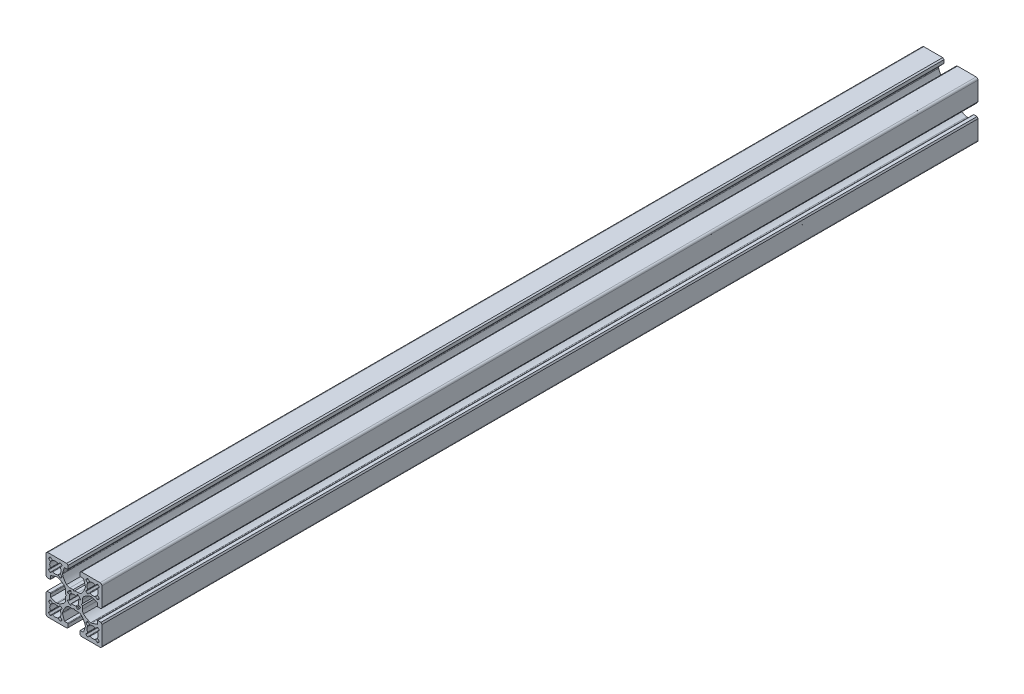
SolidWorks part; units mm, degrees
ref_plane "정면" through (0, 0, 0) normal (0, 0, 1) x (1, 0, 0)
ref_plane "윗면" through (0, 0, 0) normal (0, 1, 0) x (1, 0, 0)
ref_plane "우측면" through (0, 0, 0) normal (1, 0, 0) x (0, 0, -1)
sketch "Model" plane through (0, 0, 0) normal (0, 0, 1) x (1, 0, 0)
  line L0 (465.6218, 205.5838) -> (465.6218, 209.9838) construction
  line L1 (463.4218, 207.7838) -> (467.8218, 207.7838) construction
  line L2 (462.8793, 206.102) -> (462.1388, 205.3614)
  line L3 (463.1994, 204.3007) -> (463.94, 205.0413)
  line L4 (467.3037, 205.0413) -> (468.0443, 204.3007)
  line L5 (469.1049, 205.3614) -> (468.3643, 206.102)
  line L6 (468.3643, 209.4657) -> (469.1049, 210.2063)
  line L7 (468.0443, 211.2669) -> (467.3037, 210.5263)
  line L8 (463.94, 210.5263) -> (463.1994, 211.2669)
  line L9 (462.1388, 210.2063) -> (462.8793, 209.4657)
  line L10 (463.4211, 187.7832) -> (467.8211, 187.7829) construction
  line L11 (465.6212, 189.9831) -> (465.6209, 185.5831) construction
  line L12 (462.8787, 189.4651) -> (462.1382, 190.2057)
  line L13 (463.1989, 191.2663) -> (463.9394, 190.5257)
  line L14 (467.3031, 190.5254) -> (468.0438, 191.2659)
  line L15 (469.1043, 190.2052) -> (468.3637, 189.4647)
  line L16 (468.3634, 186.101) -> (469.1039, 185.3604)
  line L17 (468.0432, 184.2998) -> (467.3027, 185.0404)
  line L18 (463.939, 185.0407) -> (463.1984, 184.3002)
  line L19 (462.1378, 185.3609) -> (462.8784, 186.1014)
  line L20 (448.3673, 189.4651) -> (449.1078, 190.2057)
  line L21 (448.0471, 191.2663) -> (447.3066, 190.5257)
  line L22 (443.9429, 190.5254) -> (443.2023, 191.2659)
  line L23 (442.1417, 190.2052) -> (442.8823, 189.4647)
  line L24 (442.8826, 186.101) -> (442.1421, 185.3604)
  line L25 (443.2028, 184.2998) -> (443.9433, 185.0404)
  line L26 (447.307, 185.0407) -> (448.0476, 184.3002)
  line L27 (449.1082, 185.3609) -> (448.3676, 186.1014)
  line L28 (445.6248, 189.9831) -> (445.6251, 185.5831) construction
  line L29 (447.825, 187.7832) -> (443.425, 187.7829) construction
  line L30 (447.8242, 207.7838) -> (443.4242, 207.7838) construction
  line L31 (445.6242, 205.5838) -> (445.6242, 209.9838) construction
  line L32 (471.0819, 197.7838) -> (439.4, 197.7838) construction
  line L33 (455.6242, 181.8427) -> (455.6242, 213.7801) construction
  line L34 (457.2103, 201.0212) -> (457.0767, 200.2802)
  line L35 (454.1716, 200.2802) -> (454.0381, 201.0212)
  line L36 (452.3868, 199.37) -> (453.1278, 199.2364)
  line L37 (453.1278, 196.3313) -> (452.3868, 196.1977)
  line L38 (454.0381, 194.5465) -> (454.1716, 195.2874)
  line L39 (457.0767, 195.2874) -> (457.2103, 194.5465)
  line L40 (458.8615, 196.1977) -> (458.1206, 196.3313)
  line L41 (458.1206, 199.2364) -> (458.8615, 199.37)
  line L42 (448.3667, 206.102) -> (449.1073, 205.3614)
  line L43 (448.0466, 204.3007) -> (447.306, 205.0413)
  line L44 (443.9423, 205.0413) -> (443.2018, 204.3007)
  line L45 (442.1411, 205.3614) -> (442.8817, 206.102)
  line L46 (442.8817, 209.4657) -> (442.1411, 210.2063)
  line L47 (443.2018, 211.2669) -> (443.9423, 210.5263)
  line L48 (447.306, 210.5263) -> (448.0466, 211.2669)
  line L49 (449.1073, 210.2063) -> (448.3667, 209.4657)
  line L50 (459.5742, 182.7838) -> (458.7742, 183.2838)
  line L51 (458.7742, 183.2838) -> (458.7742, 184.9838)
  line L52 (459.0742, 185.2838) -> (460.7242, 185.2838)
  line L53 (460.7242, 185.2838) -> (461.7118, 188.3356)
  line L54 (457.842, 193.2838) -> (456.1242, 193.2838)
  line L55 (456.1242, 193.2838) -> (455.6242, 193.7838)
  line L56 (455.6242, 193.7838) -> (455.1242, 193.2838)
  line L57 (455.1242, 193.2838) -> (453.4063, 193.2838)
  line L58 (449.5366, 188.3356) -> (450.5242, 185.2838)
  line L59 (450.5242, 185.2838) -> (452.1742, 185.2838)
  line L60 (452.4742, 184.9838) -> (452.4742, 183.2838)
  line L61 (452.4742, 183.2838) -> (451.6742, 182.7838)
  line L62 (451.6742, 182.7838) -> (441.6242, 182.7838)
  line L63 (440.6242, 183.7838) -> (440.6242, 193.8338)
  line L64 (440.6242, 193.8338) -> (441.1242, 194.6338)
  line L65 (441.1242, 194.6338) -> (442.8242, 194.6338)
  line L66 (443.1242, 194.3338) -> (443.1242, 192.6838)
  line L67 (443.1242, 192.6838) -> (446.1759, 191.6962)
  line L68 (451.1242, 195.566) -> (451.1242, 197.2838)
  line L69 (451.1242, 197.2838) -> (451.6242, 197.7838)
  line L70 (451.6242, 197.7838) -> (451.1242, 198.2838)
  line L71 (451.1242, 198.2838) -> (451.1242, 200.0017)
  line L72 (446.1759, 203.8714) -> (443.1242, 202.8838)
  line L73 (443.1242, 202.8838) -> (443.1242, 201.2338)
  line L74 (442.8242, 200.9338) -> (441.1242, 200.9338)
  line L75 (441.1242, 200.9338) -> (440.6242, 201.7338)
  line L76 (440.6242, 201.7338) -> (440.6242, 211.7838)
  line L77 (441.6242, 212.7838) -> (451.6742, 212.7838)
  line L78 (451.6742, 212.7838) -> (452.4742, 212.2838)
  line L79 (452.4742, 212.2838) -> (452.4742, 210.5838)
  line L80 (452.1742, 210.2838) -> (450.5242, 210.2838)
  line L81 (450.5242, 210.2838) -> (449.5366, 207.2321)
  line L82 (453.4063, 202.2838) -> (455.1242, 202.2838)
  line L83 (455.1242, 202.2838) -> (455.6242, 201.7838)
  line L84 (455.6242, 201.7838) -> (456.1242, 202.2838)
  line L85 (456.1242, 202.2838) -> (457.842, 202.2838)
  line L86 (461.7118, 207.2321) -> (460.7242, 210.2838)
  line L87 (460.7242, 210.2838) -> (459.0742, 210.2838)
  line L88 (458.7742, 210.5838) -> (458.7742, 212.2838)
  line L89 (458.7742, 212.2838) -> (459.5742, 212.7838)
  line L90 (459.5742, 212.7838) -> (469.6242, 212.7838)
  line L91 (470.6242, 211.7838) -> (470.6242, 201.7338)
  line L92 (470.6242, 201.7338) -> (470.1242, 200.9338)
  line L93 (470.1242, 200.9338) -> (468.4242, 200.9338)
  line L94 (468.1242, 201.2338) -> (468.1242, 202.8838)
  line L95 (468.1242, 202.8838) -> (465.0724, 203.8714)
  line L96 (460.1242, 200.0017) -> (460.1242, 198.2838)
  line L97 (460.1242, 198.2838) -> (459.6242, 197.7838)
  line L98 (459.6242, 197.7838) -> (460.1242, 197.2838)
  line L99 (460.1242, 197.2838) -> (460.1242, 195.566)
  line L100 (465.0724, 191.6962) -> (468.1242, 192.6838)
  line L101 (468.1242, 192.6838) -> (468.1242, 194.3338)
  line L102 (468.4242, 194.6338) -> (470.1242, 194.6338)
  line L103 (470.1242, 194.6338) -> (470.6242, 193.8338)
  line L104 (470.6242, 193.8338) -> (470.6242, 183.7838)
  line L105 (469.6242, 182.7838) -> (459.5742, 182.7838)
  arc A0 (462.8793, 206.102) -> (462.9358, 206.4477) centre (462.6672, 206.3141) ccw
  arc A1 (462.1388, 205.3614) -> (462.1172, 204.9611) centre (462.3509, 205.1493) ccw
  arc A2 (462.1172, 204.9611) -> (462.7991, 204.2792) centre (465.6218, 207.7838) ccw
  arc A3 (462.7991, 204.2792) -> (463.1994, 204.3007) centre (462.9873, 204.5129) ccw
  arc A4 (464.2857, 205.0978) -> (463.94, 205.0413) centre (464.1521, 204.8292) ccw
  arc A5 (464.2857, 205.0978) -> (466.9579, 205.0978) centre (465.6218, 207.7838) ccw
  arc A6 (467.3037, 205.0413) -> (466.9579, 205.0978) centre (467.0916, 204.8292) ccw
  arc A7 (468.0443, 204.3007) -> (468.4446, 204.2792) centre (468.2564, 204.5129) ccw
  arc A8 (468.4446, 204.2792) -> (469.1264, 204.9611) centre (465.6218, 207.7838) ccw
  arc A9 (469.1264, 204.9611) -> (469.1049, 205.3614) centre (468.8928, 205.1493) ccw
  arc A10 (468.3079, 206.4477) -> (468.3643, 206.102) centre (468.5765, 206.3141) ccw
  arc A11 (468.3079, 206.4477) -> (468.3079, 209.1199) centre (465.6218, 207.7838) ccw
  arc A12 (468.3643, 209.4657) -> (468.3079, 209.1199) centre (468.5765, 209.2536) ccw
  arc A13 (469.1049, 210.2063) -> (469.1264, 210.6066) centre (468.8928, 210.4184) ccw
  arc A14 (469.1264, 210.6066) -> (468.4446, 211.2884) centre (465.6218, 207.7838) ccw
  arc A15 (468.4446, 211.2884) -> (468.0443, 211.2669) centre (468.2564, 211.0548) ccw
  arc A16 (466.9579, 210.4699) -> (467.3037, 210.5263) centre (467.0916, 210.7385) ccw
  arc A17 (466.9579, 210.4699) -> (464.2857, 210.4699) centre (465.6218, 207.7838) ccw
  arc A18 (463.94, 210.5263) -> (464.2857, 210.4699) centre (464.1521, 210.7385) ccw
  arc A19 (463.1994, 211.2669) -> (462.7991, 211.2884) centre (462.9873, 211.0548) ccw
  arc A20 (462.7991, 211.2884) -> (462.1172, 210.6066) centre (465.6218, 207.7838) ccw
  arc A21 (462.1172, 210.6066) -> (462.1388, 210.2063) centre (462.3509, 210.4184) ccw
  arc A22 (462.9358, 209.1199) -> (462.8793, 209.4657) centre (462.6672, 209.2536) ccw
  arc A23 (462.9358, 209.1199) -> (462.9358, 206.4477) centre (465.6218, 207.7838) ccw
  arc A24 (462.9351, 189.1194) -> (462.8787, 189.4651) centre (462.6665, 189.253) ccw
  arc A25 (462.1167, 190.6061) -> (462.1382, 190.2057) centre (462.3503, 190.4179) ccw
  arc A26 (462.7986, 191.2879) -> (462.1167, 190.6061) centre (465.6211, 187.7831) ccw
  arc A27 (463.1989, 191.2663) -> (462.7986, 191.2879) centre (462.9868, 191.0542) ccw
  arc A28 (463.9394, 190.5257) -> (464.2852, 190.4692) centre (464.1516, 190.7378) ccw
  arc A29 (466.9574, 190.469) -> (464.2852, 190.4692) centre (465.6211, 187.7831) ccw
  arc A30 (466.9574, 190.469) -> (467.3031, 190.5254) centre (467.091, 190.7376) ccw
  arc A31 (468.4441, 191.2874) -> (468.0438, 191.2659) centre (468.2559, 191.0538) ccw
  arc A32 (469.1259, 190.6055) -> (468.4441, 191.2874) centre (465.6211, 187.7831) ccw
  arc A33 (469.1043, 190.2052) -> (469.1259, 190.6055) centre (468.8922, 190.4174) ccw
  arc A34 (468.3637, 189.4647) -> (468.3072, 189.119) centre (468.5758, 189.2525) ccw
  arc A35 (468.307, 186.4467) -> (468.3072, 189.119) centre (465.6211, 187.7831) ccw
  arc A36 (468.307, 186.4467) -> (468.3634, 186.101) centre (468.5756, 186.3131) ccw
  arc A37 (469.1254, 184.96) -> (469.1039, 185.3604) centre (468.8918, 185.1482) ccw
  arc A38 (468.4435, 184.2782) -> (469.1254, 184.96) centre (465.6211, 187.7831) ccw
  arc A39 (468.0432, 184.2998) -> (468.4435, 184.2782) centre (468.2554, 184.5119) ccw
  arc A40 (467.3027, 185.0404) -> (466.957, 185.0969) centre (467.0905, 184.8283) ccw
  arc A41 (464.2847, 185.0971) -> (466.957, 185.0969) centre (465.6211, 187.7831) ccw
  arc A42 (464.2847, 185.0971) -> (463.939, 185.0407) centre (464.1511, 184.8285) ccw
  arc A43 (462.798, 184.2787) -> (463.1984, 184.3002) centre (462.9862, 184.5123) ccw
  arc A44 (462.1162, 184.9606) -> (462.798, 184.2787) centre (465.6211, 187.7831) ccw
  arc A45 (462.1378, 185.3609) -> (462.1162, 184.9606) centre (462.3499, 185.1488) ccw
  arc A46 (462.8784, 186.1014) -> (462.9349, 186.4472) centre (462.6663, 186.3136) ccw
  arc A47 (462.9351, 189.1194) -> (462.9349, 186.4472) centre (465.6211, 187.7831) ccw
  arc A48 (448.3673, 189.4651) -> (448.3109, 189.1194) centre (448.5795, 189.253) ccw
  arc A49 (449.1078, 190.2057) -> (449.1293, 190.6061) centre (448.8957, 190.4179) ccw
  arc A50 (449.1293, 190.6061) -> (448.4474, 191.2879) centre (445.625, 187.7831) ccw
  arc A51 (448.4474, 191.2879) -> (448.0471, 191.2663) centre (448.2593, 191.0542) ccw
  arc A52 (446.9609, 190.4692) -> (447.3066, 190.5257) centre (447.0944, 190.7378) ccw
  arc A53 (446.9609, 190.4692) -> (444.2886, 190.469) centre (445.625, 187.7831) ccw
  arc A54 (443.9429, 190.5254) -> (444.2886, 190.469) centre (444.155, 190.7376) ccw
  arc A55 (443.2023, 191.2659) -> (442.8019, 191.2874) centre (442.9901, 191.0538) ccw
  arc A56 (442.8019, 191.2874) -> (442.1201, 190.6055) centre (445.625, 187.7831) ccw
  arc A57 (442.1201, 190.6055) -> (442.1417, 190.2052) centre (442.3538, 190.4174) ccw
  arc A58 (442.9388, 189.119) -> (442.8823, 189.4647) centre (442.6702, 189.2525) ccw
  arc A59 (442.9388, 189.119) -> (442.939, 186.4467) centre (445.625, 187.7831) ccw
  arc A60 (442.8826, 186.101) -> (442.939, 186.4467) centre (442.6704, 186.3131) ccw
  arc A61 (442.1421, 185.3604) -> (442.1206, 184.96) centre (442.3542, 185.1482) ccw
  arc A62 (442.1206, 184.96) -> (442.8025, 184.2782) centre (445.625, 187.7831) ccw
  arc A63 (442.8025, 184.2782) -> (443.2028, 184.2998) centre (442.9907, 184.5119) ccw
  arc A64 (444.2891, 185.0969) -> (443.9433, 185.0404) centre (444.1555, 184.8283) ccw
  arc A65 (444.2891, 185.0969) -> (446.9613, 185.0971) centre (445.625, 187.7831) ccw
  arc A66 (447.307, 185.0407) -> (446.9613, 185.0971) centre (447.0949, 184.8285) ccw
  arc A67 (448.0476, 184.3002) -> (448.448, 184.2787) centre (448.2598, 184.5123) ccw
  arc A68 (448.448, 184.2787) -> (449.1298, 184.9606) centre (445.625, 187.7831) ccw
  arc A69 (449.1298, 184.9606) -> (449.1082, 185.3609) centre (448.8961, 185.1488) ccw
  arc A70 (448.3111, 186.4472) -> (448.3676, 186.1014) centre (448.5797, 186.3136) ccw
  arc A71 (448.3111, 186.4472) -> (448.3109, 189.1194) centre (445.625, 187.7831) ccw
  arc A72 (458.8615, 199.37) -> (459.0666, 199.8178) centre (458.8083, 199.6652) ccw
  arc A73 (459.0666, 199.8178) -> (457.6582, 201.2262) centre (455.623, 197.7827) ccw
  arc A74 (457.6582, 201.2262) -> (457.2103, 201.0212) centre (457.5055, 200.9679) ccw
  arc A75 (456.6575, 200.0603) -> (457.0767, 200.2802) centre (456.7815, 200.3335) ccw
  arc A76 (456.6575, 200.0603) -> (454.5909, 200.0603) centre (455.6242, 197.7838) ccw
  arc A77 (454.1716, 200.2802) -> (454.5909, 200.0603) centre (454.4669, 200.3335) ccw
  arc A78 (454.0381, 201.0212) -> (453.5902, 201.2262) centre (453.7428, 200.9679) ccw
  arc A79 (453.5902, 201.2262) -> (452.1818, 199.8178) centre (455.6253, 197.7827) ccw
  arc A80 (452.1818, 199.8178) -> (452.3868, 199.37) centre (452.4401, 199.6652) ccw
  arc A81 (453.3477, 198.8171) -> (453.1278, 199.2364) centre (453.0745, 198.9411) ccw
  arc A82 (453.3477, 198.8171) -> (453.3477, 196.7505) centre (455.6242, 197.7838) ccw
  arc A83 (453.1278, 196.3313) -> (453.3477, 196.7505) centre (453.0745, 196.6265) ccw
  arc A84 (452.3868, 196.1977) -> (452.1818, 195.7498) centre (452.4401, 195.9025) ccw
  arc A85 (452.1818, 195.7498) -> (453.5902, 194.3414) centre (455.6253, 197.785) ccw
  arc A86 (453.5902, 194.3414) -> (454.0381, 194.5465) centre (453.7428, 194.5997) ccw
  arc A87 (454.5909, 195.5074) -> (454.1716, 195.2874) centre (454.4669, 195.2342) ccw
  arc A88 (454.5909, 195.5074) -> (456.6575, 195.5074) centre (455.6242, 197.7838) ccw
  arc A89 (457.0767, 195.2874) -> (456.6575, 195.5074) centre (456.7815, 195.2342) ccw
  arc A90 (457.2103, 194.5465) -> (457.6582, 194.3414) centre (457.5055, 194.5997) ccw
  arc A91 (457.6582, 194.3414) -> (459.0666, 195.7498) centre (455.623, 197.785) ccw
  arc A92 (459.0666, 195.7498) -> (458.8615, 196.1977) centre (458.8083, 195.9025) ccw
  arc A93 (457.9006, 196.7505) -> (458.1206, 196.3313) centre (458.1738, 196.6265) ccw
  arc A94 (457.9006, 196.7505) -> (457.9006, 198.8171) centre (455.6242, 197.7838) ccw
  arc A95 (458.1206, 199.2364) -> (457.9006, 198.8171) centre (458.1738, 198.9411) ccw
  arc A96 (448.3102, 206.4477) -> (448.3667, 206.102) centre (448.5788, 206.3141) ccw
  arc A97 (449.1288, 204.9611) -> (449.1073, 205.3614) centre (448.8951, 205.1493) ccw
  arc A98 (448.4469, 204.2792) -> (449.1288, 204.9611) centre (445.6242, 207.7838) ccw
  arc A99 (448.0466, 204.3007) -> (448.4469, 204.2792) centre (448.2587, 204.5129) ccw
  arc A100 (447.306, 205.0413) -> (446.9603, 205.0978) centre (447.0939, 204.8292) ccw
  arc A101 (444.2881, 205.0978) -> (446.9603, 205.0978) centre (445.6242, 207.7838) ccw
  arc A102 (444.2881, 205.0978) -> (443.9423, 205.0413) centre (444.1545, 204.8292) ccw
  arc A103 (442.8014, 204.2792) -> (443.2018, 204.3007) centre (442.9896, 204.5129) ccw
  arc A104 (442.1196, 204.9611) -> (442.8014, 204.2792) centre (445.6242, 207.7838) ccw
  arc A105 (442.1411, 205.3614) -> (442.1196, 204.9611) centre (442.3532, 205.1493) ccw
  arc A106 (442.8817, 206.102) -> (442.9381, 206.4477) centre (442.6695, 206.3141) ccw
  arc A107 (442.9381, 209.1199) -> (442.9381, 206.4477) centre (445.6242, 207.7838) ccw
  arc A108 (442.9381, 209.1199) -> (442.8817, 209.4657) centre (442.6695, 209.2536) ccw
  arc A109 (442.1196, 210.6066) -> (442.1411, 210.2063) centre (442.3532, 210.4184) ccw
  arc A110 (442.8014, 211.2884) -> (442.1196, 210.6066) centre (445.6242, 207.7838) ccw
  arc A111 (443.2018, 211.2669) -> (442.8014, 211.2884) centre (442.9896, 211.0548) ccw
  arc A112 (443.9423, 210.5263) -> (444.2881, 210.4699) centre (444.1545, 210.7385) ccw
  arc A113 (446.9603, 210.4699) -> (444.2881, 210.4699) centre (445.6242, 207.7838) ccw
  arc A114 (446.9603, 210.4699) -> (447.306, 210.5263) centre (447.0939, 210.7385) ccw
  arc A115 (448.4469, 211.2884) -> (448.0466, 211.2669) centre (448.2587, 211.0548) ccw
  arc A116 (449.1288, 210.6066) -> (448.4469, 211.2884) centre (445.6242, 207.7838) ccw
  arc A117 (449.1073, 210.2063) -> (449.1288, 210.6066) centre (448.8951, 210.4184) ccw
  arc A118 (448.3667, 209.4657) -> (448.3102, 209.1199) centre (448.5788, 209.2536) ccw
  arc A119 (448.3102, 206.4477) -> (448.3102, 209.1199) centre (445.6242, 207.7838) ccw
  arc A120 (459.0742, 185.2838) -> (458.7742, 184.9838) centre (459.0742, 184.9838) ccw
  arc A121 (461.7118, 188.3356) -> (461.7375, 188.856) centre (460.7604, 188.6435) ccw
  arc A122 (461.7375, 188.856) -> (459.6282, 192.6941) centre (452.2648, 186.1487) ccw
  arc A123 (459.6282, 192.6941) -> (457.842, 193.2838) centre (457.842, 190.2838) ccw
  arc A124 (453.4063, 193.2838) -> (451.6202, 192.6941) centre (453.4063, 190.2838) ccw
  arc A125 (451.6202, 192.6941) -> (449.5108, 188.856) centre (458.9836, 186.1487) ccw
  arc A126 (449.5108, 188.856) -> (449.5366, 188.3356) centre (450.488, 188.6435) ccw
  arc A127 (452.4742, 184.9838) -> (452.1742, 185.2838) centre (452.1742, 184.9838) ccw
  arc A128 (440.6242, 183.7838) -> (441.6242, 182.7838) centre (441.6242, 183.7838) ccw
  arc A129 (443.1242, 194.3338) -> (442.8242, 194.6338) centre (442.8242, 194.3338) ccw
  arc A130 (446.1759, 191.6962) -> (446.6963, 191.6705) centre (446.4838, 192.6476) ccw
  arc A131 (446.6963, 191.6705) -> (450.5345, 193.7798) centre (443.9891, 201.1432) ccw
  arc A132 (450.5345, 193.7798) -> (451.1242, 195.566) centre (448.1242, 195.566) ccw
  arc A133 (451.1242, 200.0017) -> (450.5345, 201.7878) centre (448.1242, 200.0017) ccw
  arc A134 (450.5345, 201.7878) -> (446.6963, 203.8972) centre (443.9891, 194.4244) ccw
  arc A135 (446.6963, 203.8972) -> (446.1759, 203.8714) centre (446.4838, 202.92) ccw
  arc A136 (442.8242, 200.9338) -> (443.1242, 201.2338) centre (442.8242, 201.2338) ccw
  arc A137 (441.6242, 212.7838) -> (440.6242, 211.7838) centre (441.6242, 211.7838) ccw
  arc A138 (452.1742, 210.2838) -> (452.4742, 210.5838) centre (452.1742, 210.5838) ccw
  arc A139 (449.5366, 207.2321) -> (449.5108, 206.7117) centre (450.488, 206.9242) ccw
  arc A140 (449.5108, 206.7117) -> (451.6202, 202.8735) centre (458.9836, 209.4189) ccw
  arc A141 (451.6202, 202.8735) -> (453.4063, 202.2838) centre (453.4063, 205.2838) ccw
  arc A142 (457.842, 202.2838) -> (459.6282, 202.8735) centre (457.842, 205.2838) ccw
  arc A143 (459.6282, 202.8735) -> (461.7375, 206.7117) centre (452.2648, 209.4189) ccw
  arc A144 (461.7375, 206.7117) -> (461.7118, 207.2321) centre (460.7604, 206.9242) ccw
  arc A145 (458.7742, 210.5838) -> (459.0742, 210.2838) centre (459.0742, 210.5838) ccw
  arc A146 (470.6242, 211.7838) -> (469.6242, 212.7838) centre (469.6242, 211.7838) ccw
  arc A147 (468.1242, 201.2338) -> (468.4242, 200.9338) centre (468.4242, 201.2338) ccw
  arc A148 (465.0724, 203.8714) -> (464.552, 203.8972) centre (464.7645, 202.92) ccw
  arc A149 (464.552, 203.8972) -> (460.7139, 201.7878) centre (467.2593, 194.4244) ccw
  arc A150 (460.7139, 201.7878) -> (460.1242, 200.0017) centre (463.1242, 200.0017) ccw
  arc A151 (460.1242, 195.566) -> (460.7139, 193.7798) centre (463.1242, 195.566) ccw
  arc A152 (460.7139, 193.7798) -> (464.552, 191.6705) centre (467.2593, 201.1432) ccw
  arc A153 (464.552, 191.6705) -> (465.0724, 191.6962) centre (464.7645, 192.6476) ccw
  arc A154 (468.4242, 194.6338) -> (468.1242, 194.3338) centre (468.4242, 194.3338) ccw
  arc A155 (469.6242, 182.7838) -> (470.6242, 183.7838) centre (469.6242, 183.7838) ccw
  dimension "D1" = 30
  dimension "D2" = 30
  dimension "D3" = 15
  dimension "D4" = 15
extrude "보스-돌출1" add sketch "Model" along normal blind 470
